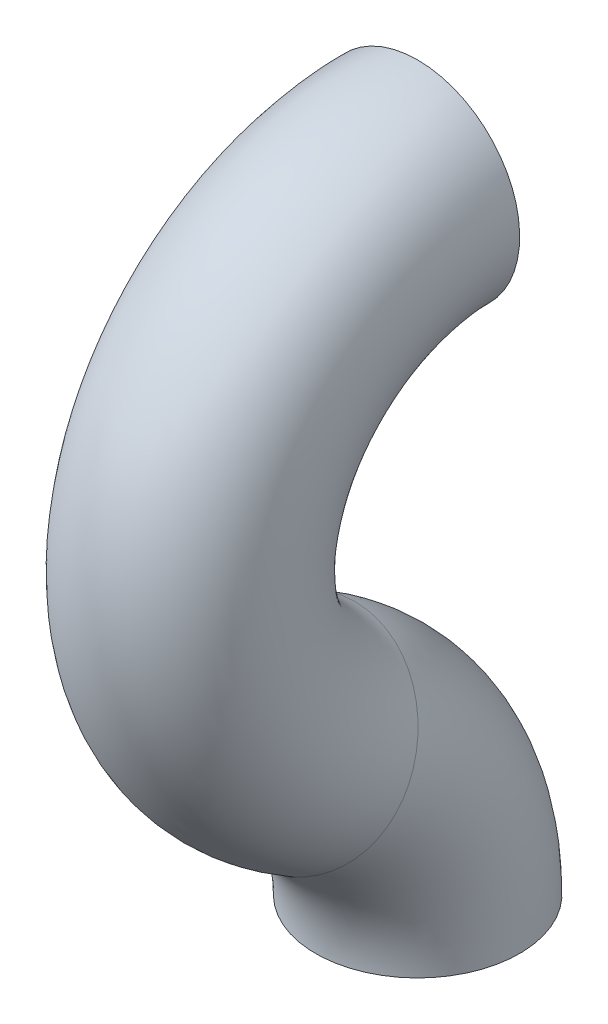
SolidWorks part; units mm, degrees
ref_plane "Front Plane" through (0, 0, 0) normal (0, 0, 1) x (1, 0, 0)
ref_plane "Top Plane" through (0, 0, 0) normal (0, 1, 0) x (1, 0, 0)
ref_plane "Right Plane" through (0, 0, 0) normal (1, 0, 0) x (0, 0, -1)
sketch "Sketch1" plane through (0, 0, 0) normal (1, 0, 0) x (0, 0, -1)
  line L0 (0, 0) -> (0, -37.0564) construction
  line L1 (0, 140) -> (64.3168, 140) construction
  line L2 (0, 140) -> (0, 0) construction
  arc A0 (0, 0) -> (-25.6218, 44.3782) centre (-51.2436, 0) ccw
  arc A1 (-25.6218, 44.3782) -> (0, 140) centre (0, 88.7564) cw
  dimension "D1" = 140
sketch "Sketch2" plane through (0, 0, 0) normal (0, 1, 0) x (1, 0, 0)
  circle A0 centre (0, 0) radius 23
  dimension "D1" = 46
sweep "Sweep1" add profiles "Sketch2" path "Sketch1"
